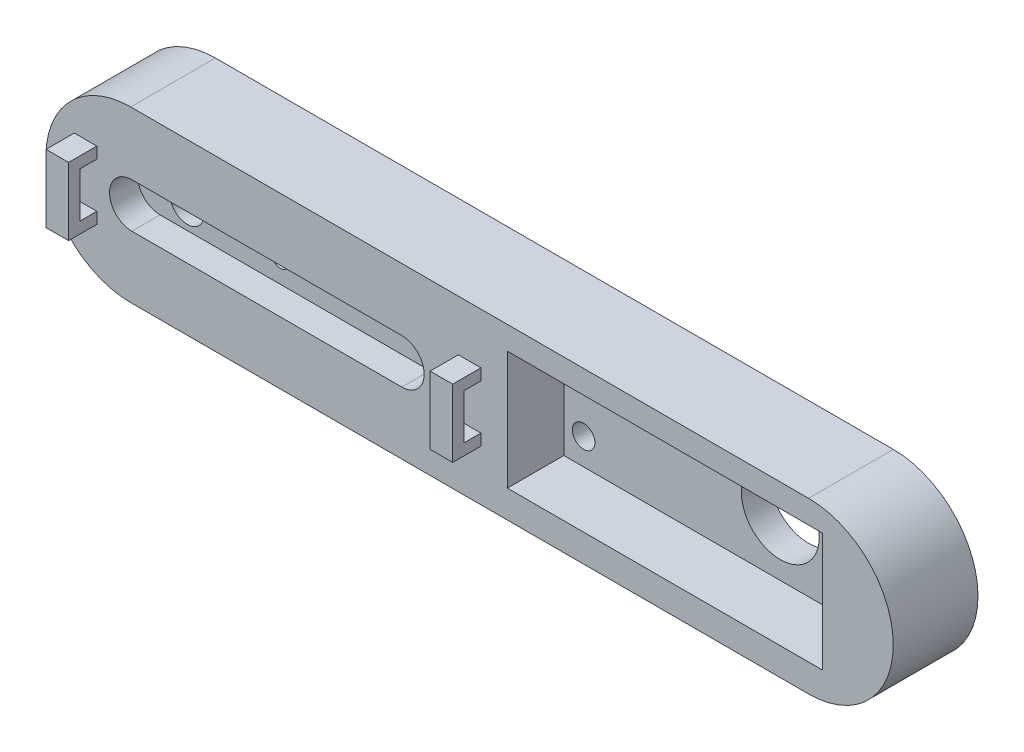
SolidWorks part; units mm, degrees
ref_plane "Front Plane" through (0, 0, 0) normal (0, 0, 1) x (1, 0, 0)
ref_plane "Top Plane" through (0, 0, 0) normal (0, 1, 0) x (1, 0, 0)
ref_plane "Right Plane" through (0, 0, 0) normal (1, 0, 0) x (0, 0, -1)
sketch "Sketch1" plane through (0, 0, 0) normal (0, 0, 1) x (1, 0, 0)
  line L0 (60, 0) -> (-60, 0) construction
  line L1 (60, -15) -> (-60, -15)
  line L2 (60, 15) -> (-60, 15)
  arc A0 (60, -15) -> (60, 15) centre (60, 0) ccw
  arc A1 (-60, 15) -> (-60, -15) centre (-60, 0) ccw
  point P2 (0, 0)
  point P8 (-60, 0)
  point P9 (60, 0)
  dimension "D1" = 120
  dimension "D2" = 30
extrude "Boss-Extrude1" add sketch "Sketch1" along normal blind 15 contours L2 A1 L1 A0
sketch "Sketch2" plane through (0, 0, 0) normal (0, 0, -1) x (-1, 0, 0)
  line L0 (-60, 0) -> (60, 0) construction
  circle A1 centre (55, 0) radius 3
  point P0 (55, 0)
  dimension "D1" = 5
extrude "Cut-Extrude1" cut sketch "Sketch2" against normal blind 10
sketch "Sketch3" plane through (0, 0, 15) normal (0, 0, 1) x (1, 0, 0)
  line L0 (6.68, 10.9) -> (6.68, -10.1)
  line L1 (6.68, -10.1) -> (62.48, -10.1)
  line L2 (62.48, -10.1) -> (62.48, 10.9)
  line L3 (62.48, 10.9) -> (6.68, 10.9)
  line L4 (60, 0) -> (-60, 0) construction
  point P0 (0, 0)
  point P1 (62.48, -10.1)
  point P3 (62.48, 10.9)
  point P4 (6.68, 10.9)
  point P5 (6.68, -10.1)
  point P6 (10.18, 5.4)
  point P7 (10.18, -4.6)
  point P8 (58.98, 5.4)
  point P9 (58.98, -4.6)
  point P20 (45, 0)
extrude "Cut-Extrude2" cut sketch "Sketch3" against normal blind 10
sketch "Sketch4" plane through (0, 0, 5) normal (0, 0, 1) x (1, 0, 0)
  circle A4 centre (45, 0) radius 6.9
  circle A5 centre (58.98, -5.4) radius 2
  circle A6 centre (58.98, 4.6) radius 2
  circle A7 centre (10.18, 4.6) radius 2
  circle A8 centre (10.18, -5.4) radius 2
  point P0 (10.18, 4.6)
  point P3 (58.98, 4.6)
  point P8 (10.18, -5.4)
  point P9 (58.98, -5.4)
extrude "Cut-Extrude3" cut sketch "Sketch4" against normal blind 5
sketch "Sketch6" plane through (0, 0, 15) normal (0, 0, 1) x (1, 0, 0)
  line L0 (-59.7977, 0) -> (-12, 0) construction
  line L1 (-59.7977, 3.9489) -> (-12, 3.9489)
  line L2 (-59.7977, -3.9489) -> (-12, -3.9489)
  arc A0 (-59.7977, 3.9489) -> (-59.7977, -3.9489) centre (-59.7977, 0) ccw
  arc A1 (-12, -3.9489) -> (-12, 3.9489) centre (-12, 0) ccw
  point P0 (-59.7977, 0)
  point P1 (-12, 0)
  point P4 (-35.8988, 0)
extrude "Cut-Extrude4" cut sketch "Sketch6" against normal blind 5
sketch "Sketch7" plane through (0, 0, 0) normal (0, 0, -1) x (-1, 0, 0)
  circle A0 centre (-58.98, 4.6) radius 3
  circle A1 centre (-58.98, -5.4) radius 3
  circle A2 centre (-10.18, 4.6) radius 3
  circle A3 centre (-10.18, -5.4) radius 3
  dimension "D1" = 48.8
extrude "Cut-Extrude5" cut sketch "Sketch7" against normal blind 2
sketch "Sketch8" plane through (0, 0, 0) normal (0, 0, -1) x (-1, 0, 0)
  line L0 (40, 0) -> (70, 0) construction
  line L1 (40, 4.65) -> (70, 4.65)
  line L2 (40, -4.65) -> (70, -4.65)
  arc A0 (40, 4.65) -> (40, -4.65) centre (40, 0) ccw
  arc A1 (70, -4.65) -> (70, 4.65) centre (70, 0) ccw
  point P2 (55, 0)
  dimension "D1" = 9.3
  dimension "D2" = 30
extrude "Cut-Extrude6" cut sketch "Sketch8" against normal blind 3
sketch "Sketch9" plane through (0, 0, 0) normal (0, 0, -1) x (-1, 0, 0)
  circle A0 centre (55, 0) radius 6.5
  dimension "D1" = 13
extrude "Cut-Extrude7" cut sketch "Sketch9" against normal blind 3
ref_point "Point1"
sketch "Sketch11" plane through (0, 0, 15) normal (0, 0, 1) x (1, 0, 0)
  line L1 (-2, 6) -> (2, 6)
  line L2 (-2, 6) -> (-2, -6)
  line L3 (-2, -6) -> (2, -6)
  line L4 (2, 6) -> (2, -6)
  line L5 (-2, 6) -> (2, -6) construction
  line L6 (-2, -6) -> (2, 6) construction
  point P0 (0, 0)
extrude "Boss-Extrude2" add sketch "Sketch11" along normal blind 5
sketch "Sketch13" plane through (2, 0, 0) normal (1, 0, 0) x (0, 0, -1)
  line L0 (-15, 0) -> (-15, 4)
  line L1 (-15, -6) -> (-15, 6) construction
  line L2 (-15, 4) -> (-18, 4)
  line L3 (-18, 4) -> (-18, -4)
  line L4 (-18, -4) -> (-15, -4)
  line L5 (-15, -4) -> (-15, 0)
extrude "Cut-Extrude9" cut sketch "Sketch13" against normal blind 4
sketch "Sketch14" plane through (0, 0, 15) normal (0, 0, 1) x (1, 0, 0)
  line L1 (-70, 6) -> (-66, 6)
  line L2 (-70, 6) -> (-70, -6)
  line L3 (-70, -6) -> (-66, -6)
  line L4 (-66, 6) -> (-66, -6)
  line L5 (-70, 6) -> (-66, -6) construction
  line L6 (-70, -6) -> (-66, 6) construction
  point P0 (-68, 0)
  point P3 (0, 0)
  point P5 (-68, 0)
extrude "Boss-Extrude3" add sketch "Sketch14" along normal blind 5 contours L2 L1 L4 L3
sketch "Sketch15" plane through (-66, 0, 0) normal (1, 0, 0) x (0, 0, -1)
  line L0 (-15, -4) -> (-15, 4)
  line L1 (-15, 4) -> (-18, 4)
  line L2 (-18, 4) -> (-18, -4)
  line L3 (-18, -4) -> (-15, -4)
extrude "Cut-Extrude10" cut sketch "Sketch15" against normal blind 4
sketch "Sketch16" plane through (0, 0, 3) normal (0, 0, -1) x (-1, 0, 0)
  circle A0 centre (38.5, 0) radius 1.5
  point P0 (55, 0)
  point P1 (71.5, 0)
  point P11 (38.5, 0)
  dimension "D1" = 16.5
extrude "Cut-Extrude11" cut sketch "Sketch16" against normal blind 7
